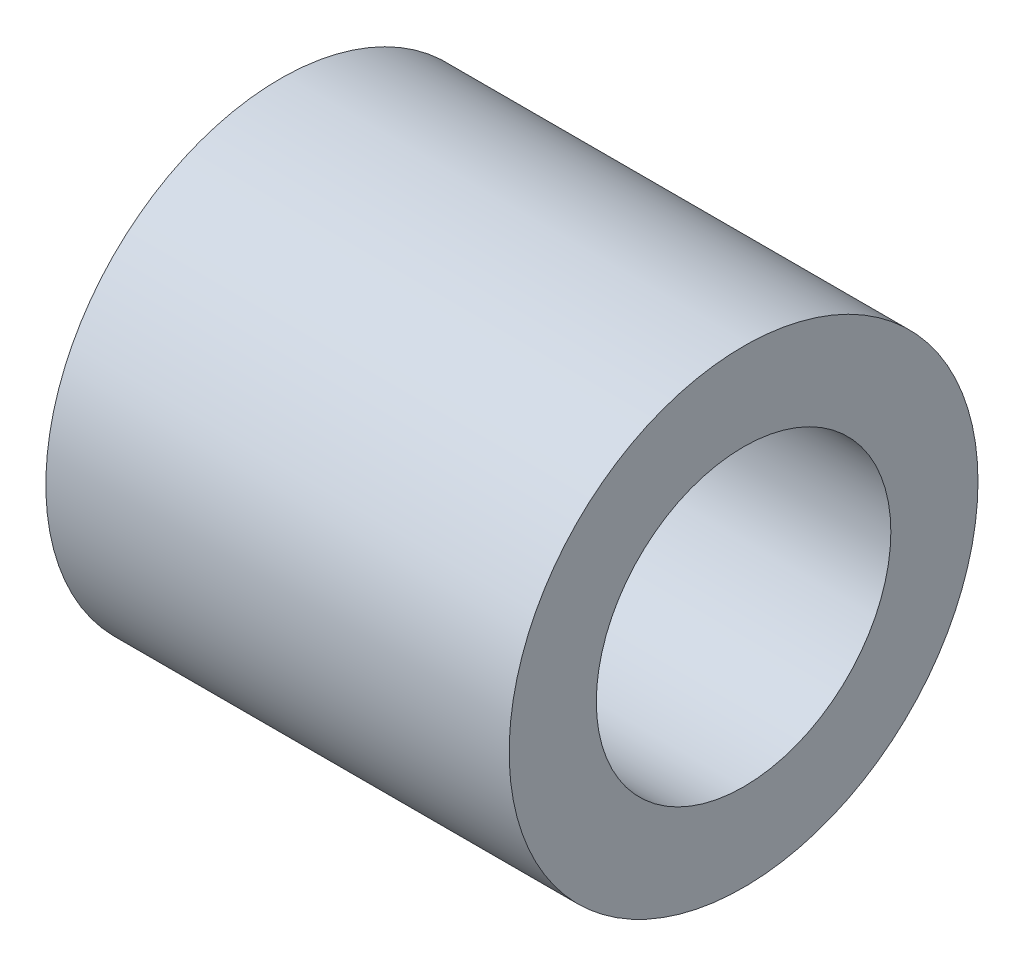
SolidWorks part; units mm, degrees
material "PLA"
ref_plane "Front Plane" through (0, 0, 0) normal (0, 0, 1) x (1, 0, 0)
ref_plane "Top Plane" through (0, 0, 0) normal (0, 1, 0) x (1, 0, 0)
ref_plane "Right Plane" through (0, 0, 0) normal (1, 0, 0) x (0, 0, -1)
sketch "Sketch1" plane through (0, 0, 0) normal (1, 0, 0) x (0, 0, -1)
  circle A0 centre (0, 0) radius 3.3909
  circle A1 centre (0, 0) radius 5.3975
  dimension "D1" = 6.7818
  dimension "D2" = 10.795
extrude "Boss-Extrude1" add sketch "Sketch1" along normal blind 10.668
